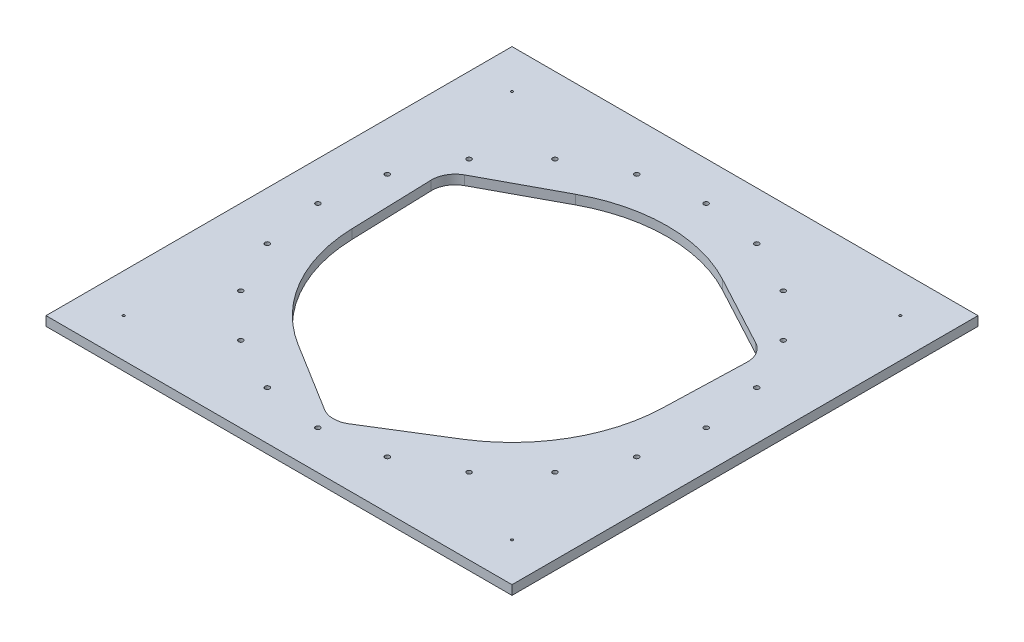
SolidWorks part; units mm, degrees
ref_plane "Front Plane" through (0, 0, 0) normal (0, 0, 1) x (1, 0, 0)
ref_plane "Top Plane" through (0, 0, 0) normal (0, 1, 0) x (1, 0, 0)
ref_plane "Right Plane" through (0, 0, 0) normal (1, 0, 0) x (0, 0, -1)
sketch "Sketch1" plane through (0, 0, 0) normal (0, 1, 0) x (1, 0, 0)
  line L0 (-203.1905, 99.0638) -> (-199.9026, -6.2414)
  line L1 (-300, 300) -> (300, 300)
  line L2 (-300, 300) -> (-300, -300)
  line L3 (-300, -300) -> (300, -300)
  line L4 (300, 300) -> (300, -300)
  line L5 (-187.387, 126.4362) -> (-94.546, 176.2414)
  line L6 (15.8035, -225.5) -> (105.3565, -170)
  line L7 (-15.8035, -225.5) -> (-105.3565, -170)
  line L8 (187.387, 126.4362) -> (94.546, 176.2414)
  line L9 (203.1905, 99.0638) -> (199.9026, -6.2414)
  line L10 (0, 491.1713) -> (0, 410.7958) construction
  line L11 (-517.8117, 0) -> (536.3525, 0) construction
  arc A0 (105.3565, -170) -> (199.9026, -6.2414) centre (0, 0) ccw
  arc A1 (-15.8035, -225.5) -> (15.8035, -225.5) centre (0, -200) ccw
  arc A2 (-187.387, 126.4362) -> (-203.1905, 99.0638) centre (-173.2051, 100) ccw
  arc A3 (203.1905, 99.0638) -> (187.387, 126.4362) centre (173.2051, 100) ccw
  arc A4 (-199.9026, -6.2414) -> (-105.3565, -170) centre (0, 0) ccw
  arc A5 (94.546, 176.2414) -> (-94.546, 176.2414) centre (0, 0) ccw
  circle A6 centre (0, 250) radius 3
  circle A7 centre (77.2542, 237.7641) radius 3
  circle A8 centre (146.9463, 202.2542) radius 3
  circle A9 centre (202.2542, 146.9463) radius 3
  circle A10 centre (237.7641, 77.2542) radius 3
  circle A11 centre (250, 0) radius 3
  circle A12 centre (237.7641, -77.2542) radius 3
  circle A13 centre (202.2542, -146.9463) radius 3
  circle A14 centre (146.9463, -202.2542) radius 3
  circle A15 centre (77.2542, -237.7641) radius 3
  circle A16 centre (0, -250) radius 3
  circle A17 centre (-77.2542, -237.7641) radius 3
  circle A18 centre (-146.9463, -202.2542) radius 3
  circle A19 centre (-202.2542, -146.9463) radius 3
  circle A20 centre (-237.7641, -77.2542) radius 3
  circle A21 centre (-250, 0) radius 3
  circle A22 centre (-237.7641, 77.2542) radius 3
  circle A23 centre (-202.2542, 146.9463) radius 3
  circle A24 centre (-146.9463, 202.2542) radius 3
  circle A25 centre (-77.2542, 237.7641) radius 3
  circle A26 centre (0, 50) radius 3
  circle A27 centre (43.3013, 25) radius 3
  circle A28 centre (43.3013, -25) radius 3
  circle A29 centre (0, -50) radius 3
  circle A30 centre (-43.3013, -25) radius 3
  circle A31 centre (-43.3013, 25) radius 3
  circle A32 centre (-250, 250) radius 1.5
  circle A33 centre (250, 250) radius 1.5
  circle A34 centre (250, -250) radius 1.5
  circle A35 centre (-250, -250) radius 1.5
  point P7 (-300, 0)
  point P8 (0, -300)
  point P26 (0, 0)
  point P67 (0, 0)
  point P79 (0, 0)
  dimension "D3" = 400
  dimension "D4" = 60
  dimension "D6" = 250
  dimension "D7" = 6
  dimension "D10" = 6
  dimension "D12" = 3
  dimension "D1" = 600
  dimension "D2" = 600
  dimension "D9" = 50
  dimension "D13" = 50
  dimension "D14" = 50
  dimension "D5" = 3
  dimension "D8" = 20
  dimension "D11" = 6
extrude "Boss-Extrude1" add sketch "Sketch1" along normal blind 12 contours L4 L1 L2 L3 A25 A24 A23 A22 A21 A20 A19 A18 A17 A16 A15 A14 A13 A12 A11 A10 A9 A8 A7 A6 A5 L8 A3 L9 A0 L6
